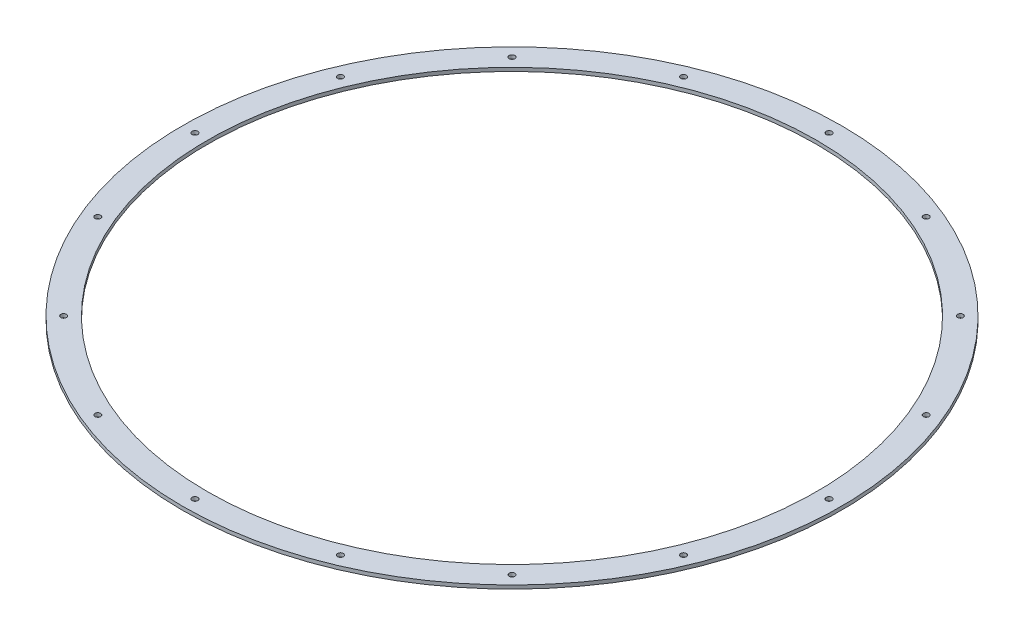
SolidWorks part; units mm, degrees
material "ASTM A36 Steel"
ref_plane "Front Plane" through (0, 0, 0) normal (0, 0, 1) x (1, 0, 0)
ref_plane "Top Plane" through (0, 0, 0) normal (0, 1, 0) x (1, 0, 0)
ref_plane "Right Plane" through (0, 0, 0) normal (1, 0, 0) x (0, 0, -1)
sketch "Sketch1" plane through (0, 0, 0) normal (0, 1, 0) x (1, 0, 0)
  circle A0 centre (0, 0) radius 460
  circle A1 centre (0, 0) radius 425
  dimension "D1" = 850
  dimension "D2" = 920
extrude "Boss-Extrude1" add sketch "Sketch1" along normal blind 5
sketch "Sketch2" plane through (0, 5, 0) normal (0, 1, 0) x (1, 0, 0)
  circle A0 centre (0, 0) radius 442.5 construction
  circle A1 centre (0, 442.5) radius 4
  dimension "D1" = 885
  dimension "D2" = 8
extrude "Cut-Extrude1" cut sketch "Sketch2" against normal blind 10
pattern_circular "CirPattern1" count 16 every 22.5 about axis through (0, 0, 0) along (0, 1, 0) of "Cut-Extrude1"
